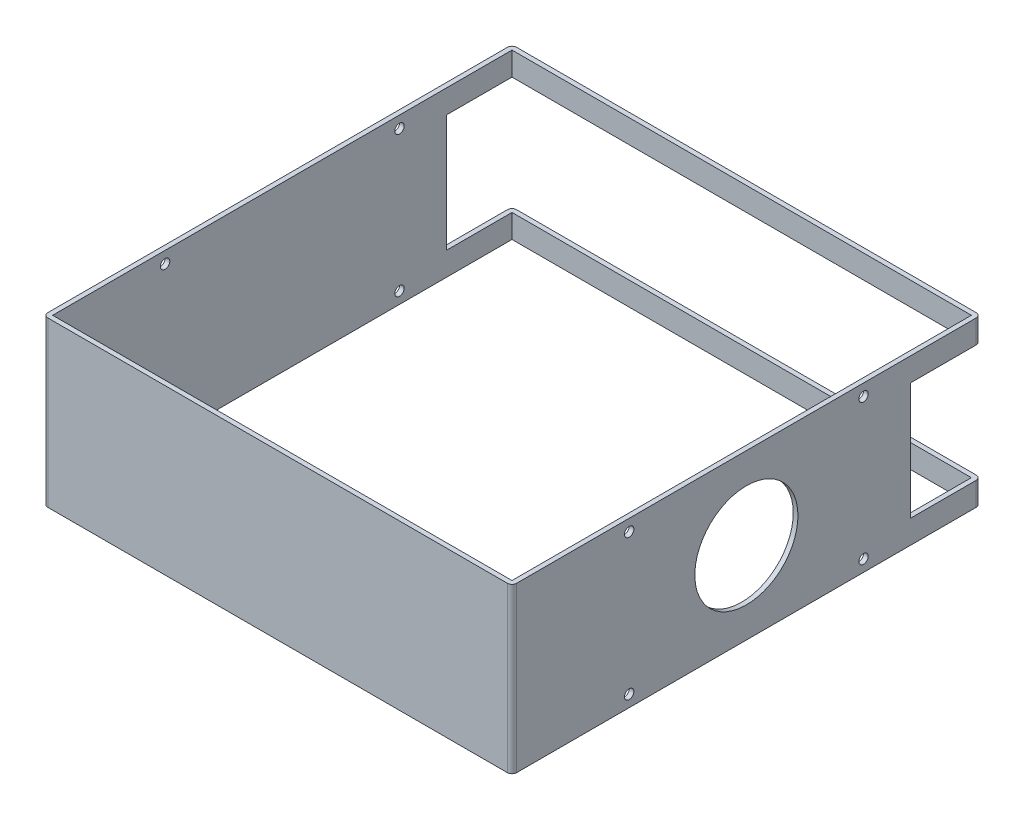
SolidWorks part; units mm, degrees
ref_plane "Front Plane" through (0, 0, 0) normal (0, 0, 1) x (1, 0, 0)
ref_plane "Top Plane" through (0, 0, 0) normal (0, 1, 0) x (1, 0, 0)
ref_plane "Right Plane" through (0, 0, 0) normal (1, 0, 0) x (0, 0, -1)
sketch "Sketch1" plane through (0, 0, 0) normal (0, 1, 0) x (1, 0, 0)
  line L1 (-50, 50) -> (50, 50)
  line L2 (-50, 50) -> (-50, -50)
  line L3 (-50, -50) -> (50, -50)
  line L4 (50, 50) -> (50, -50)
  line L5 (-50, 50) -> (50, -50) construction
  line L6 (-50, -50) -> (50, 50) construction
  point P0 (0, 0)
  dimension "D1" = 100
  dimension "D2" = 100
extrude "Boss-Extrude1" add sketch "Sketch1" along normal blind 35
sketch "Sketch2" plane through (0, 35, 0) normal (0, 1, 0) x (1, 0, 0)
  line L1 (-49, 49) -> (49, 49)
  line L2 (-49, 49) -> (-49, -49)
  line L3 (-49, -49) -> (49, -49)
  line L4 (49, 49) -> (49, -49)
  line L5 (-49, 49) -> (49, -49) construction
  line L6 (-49, -49) -> (49, 49) construction
  point P0 (0, 0)
  dimension "D1" = 98
  dimension "D2" = 98
extrude "Cut-Extrude1" cut sketch "Sketch2" against normal blind 35
ref_plane "Plane1" through (0, 0, -50) normal (0, 0, -1) x (-1, 0, 0)
sketch "Sketch5" plane through (0, 0, -50) normal (0, 0, -1) x (-1, 0, 0)
  line L0 (0, 35) -> (0, 0)
  line L1 (-50, 35) -> (50, 35) construction
  line L2 (50, 35) -> (50, 0) construction
  line L3 (-50, 30) -> (50, 30)
  line L4 (-50, 30) -> (-50, 5)
  line L5 (-50, 5) -> (50, 5)
  line L6 (50, 30) -> (50, 5)
  line L7 (-50, 30) -> (50, 5) construction
  line L8 (-50, 5) -> (50, 30) construction
  point P5 (0, 17.5)
extrude "Cut-Extrude2" cut sketch "Sketch5" against normal blind 15 contours L4 L5 L0 L3 | L6 L3 L0 L5
sketch "Sketch6" plane through (-50, 0, 0) normal (-1, 0, 0) x (0, 0, 1)
  line L0 (50, 35) -> (50, 0) construction
  line L1 (-50, 35) -> (50, 35) construction
  line L2 (-50, 35) -> (-50, 30) construction
  line L3 (-50, 30) -> (50, 30) construction
  line L4 (50, 35) -> (50, 30) construction
  line L5 (-50, 32.5) -> (0, 32.5) construction
  line L6 (0, 32.5) -> (0, 35)
  line L7 (-35, 17.5) -> (-29.6768, 17.5)
  line L8 (-35, 30) -> (-35, 5) construction
  circle A0 centre (-25, 32.5) radius 1
  circle A1 centre (25, 32.5) radius 1
  circle A2 centre (25, 2.5) radius 1
  circle A3 centre (-25, 2.5) radius 1
  dimension "D1" = 2
extrude "Cut-Extrude4" cut sketch "Sketch6" against normal blind 114 contours A0 | A1 | A3 | A2
sketch "Sketch7" plane through (50, 0, 0) normal (1, 0, 0) x (0, 0, -1)
  line L0 (-25, 32.5) -> (25, 2.5) construction
  line L1 (-25, 32.5) -> (25, 32.5) construction
  line L2 (-25, 32.5) -> (-25, 2.5) construction
  line L3 (-25, 2.5) -> (25, 2.5) construction
  line L4 (25, 32.5) -> (25, 2.5) construction
  line L5 (25, 32.5) -> (-25, 2.5) construction
  circle A0 centre (0, 17.5) radius 11
  dimension "D1" = 22
extrude "Cut-Extrude5" cut sketch "Sketch7" against normal blind 10
fillet "Fillet1" radius 1 6 edges at (-50, 17.5, 50) (-50, 32.5, -50) (-50, 2.5, -50) (50, 2.5, -50) (50, 32.5, -50) (50, 17.5, 50)
